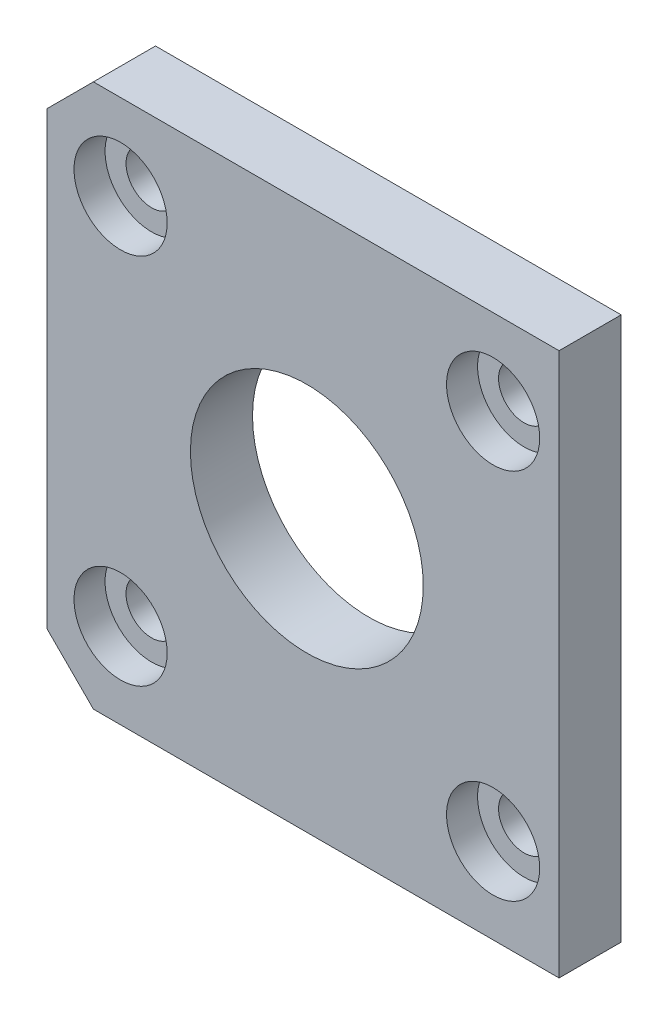
SolidWorks part; units mm, degrees
ref_plane "前视基准面" through (0, 0, 0) normal (0, 0, 1) x (1, 0, 0)
ref_plane "上视基准面" through (0, 0, 0) normal (0, 1, 0) x (1, 0, 0)
ref_plane "右视基准面" through (0, 0, 0) normal (1, 0, 0) x (0, 0, -1)
sketch "草图1" plane through (0, 0, 0) normal (0, 0, 1) x (1, 0, 0)
  line L0 (0, 32) -> (3, 35)
  line L1 (3, 0) -> (33, 0)
  line L2 (0, 3) -> (0, 32)
  line L3 (3, 35) -> (33, 35)
  line L4 (33, 0) -> (33, 35)
  line L5 (0, 3) -> (3, 0)
  circle A0 centre (16.75, 17.5) radius 7.5
  circle A1 centre (4.75, 29.5) radius 1.65
  circle A2 centre (28.75, 29.5) radius 1.65
  circle A3 centre (4.75, 5.5) radius 1.65
  circle A4 centre (28.75, 5.5) radius 1.65
  point P0 (0, 0)
  point P2 (0, 35)
  point P16 (0, 0)
  point P17 (0, 0)
  point P18 (0, 0)
  point P19 (0, 0)
  point P23 (4.5, 3.7592)
  point P24 (0, 17.5)
  dimension "D3" = 15
  dimension "D8" = 3.3
  dimension "D1" = 33
  dimension "D2" = 35
  dimension "D4" = 12
  dimension "D5" = 12
  dimension "D6" = 12
  dimension "D7" = 12
  dimension "D9" = 16.75
extrude "凸台-拉伸1" add sketch "草图1" along normal blind 4
sketch "草图2" plane through (0, 0, 4) normal (0, 0, 1) x (1, 0, 0)
  circle A0 centre (4.75, 29.5) radius 3
  circle A1 centre (28.75, 29.5) radius 3
  circle A2 centre (4.75, 5.5) radius 3
  circle A3 centre (28.75, 5.5) radius 3
  dimension "D1" = 6
extrude "切除-拉伸1" cut sketch "草图2" against normal blind 2
